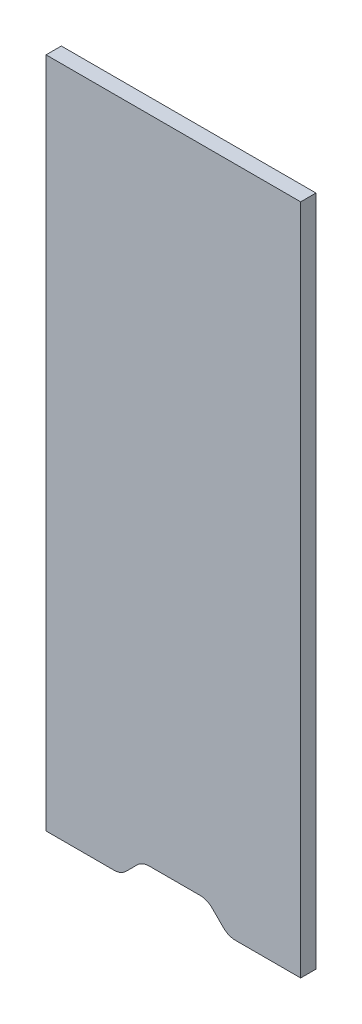
SolidWorks part; units mm, degrees
material "Teak"
ref_plane "Front Plane" through (0, 0, 0) normal (0, 0, 1) x (1, 0, 0)
ref_plane "Top Plane" through (0, 0, 0) normal (0, 1, 0) x (1, 0, 0)
ref_plane "Right Plane" through (0, 0, 0) normal (1, 0, 0) x (0, 0, -1)
sketch "Sketch1" plane through (0, 0, 0) normal (0, 0, 1) x (1, 0, 0)
  line L0 (208.9949, 5.8579) -> (195.7107, 19.1421)
  line L1 (0, 0) -> (80, 0)
  line L2 (0, 0) -> (0, 792)
  line L3 (0, 792) -> (300, 792)
  line L4 (300, 0) -> (300, 792)
  line L5 (181.5685, 25) -> (121.5685, 25)
  line L6 (107.4264, 19.1421) -> (94.1421, 5.8579)
  line L7 (223.1371, 0) -> (300, 0)
  arc A0 (94.1421, 5.8579) -> (80, 0) centre (80, 20) cw
  arc A1 (195.7107, 19.1421) -> (181.5685, 25) centre (181.5685, 5) ccw
  arc A2 (121.5685, 25) -> (107.4264, 19.1421) centre (121.5685, 5) ccw
  arc A3 (208.9949, 5.8579) -> (223.1371, 0) centre (223.1371, 20) ccw
  point P17 (214.8528, 0)
  dimension "D3" = 20
  dimension "D1" = 300
  dimension "D2" = 792
  dimension "D4" = 60
  dimension "D6" = 25
extrude "Boss-Extrude1" add sketch "Sketch1" along normal blind 18
